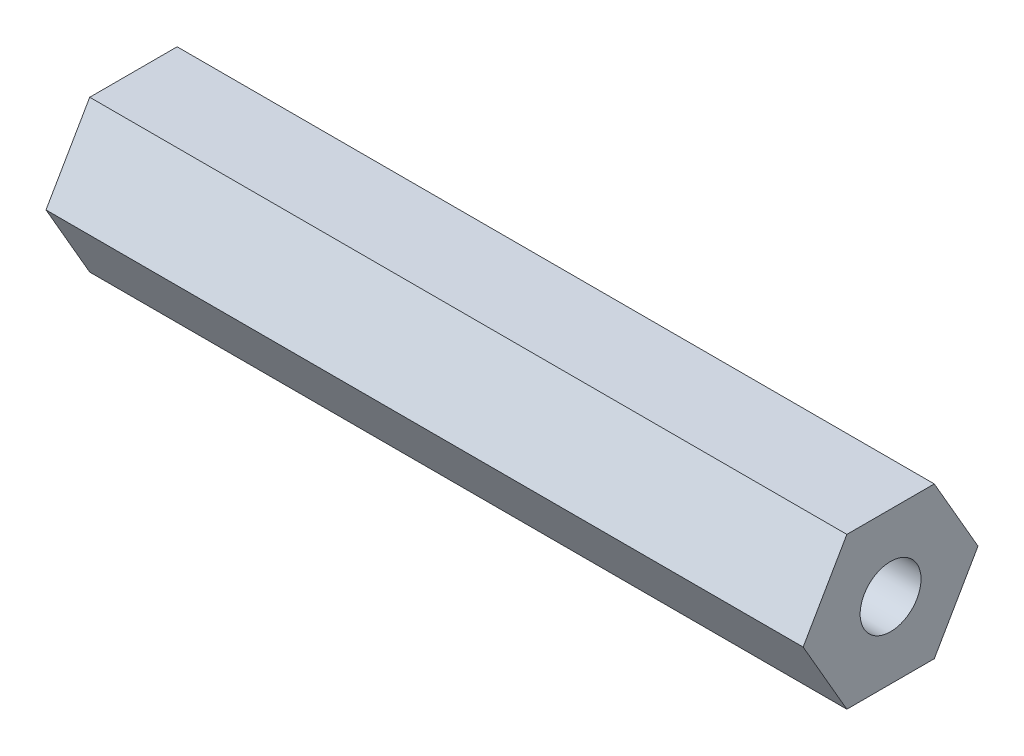
SolidWorks part; units mm, degrees
material "Plain Carbon Steel"
ref_plane "Front Plane" through (0, 0, 0) normal (0, 0, 1) x (1, 0, 0)
ref_plane "Top Plane" through (0, 0, 0) normal (0, 1, 0) x (1, 0, 0)
ref_plane "Right Plane" through (0, 0, 0) normal (1, 0, 0) x (0, 0, -1)
sketch "Sketch1" plane through (0, 0, 0) normal (1, 0, 0) x (0, 0, -1)
  line L1 (7.3323, 0) -> (3.6662, 6.35)
  line L2 (3.6662, 6.35) -> (-3.6662, 6.35)
  line L3 (-3.6662, 6.35) -> (-7.3323, 0)
  line L4 (-7.3323, 0) -> (-3.6662, -6.35)
  line L5 (-3.6662, -6.35) -> (3.6662, -6.35)
  line L6 (3.6662, -6.35) -> (7.3323, 0)
  circle A0 centre (0, 0) radius 6.35 construction
  dimension "D1" = 12.7
extrude "Boss-Extrude1" add sketch "Sketch1" along normal blind 63.5
hole_wizard "1/4-20 Tapped Hole1" positions "Sketch3" profile "Sketch4" tap size "1/4-20" standard "ANSI Inch"
sketch "Sketch3" plane through (63.5, 0, 0) normal (1, 0, 0) x (0, 0, -1)
  point P0 (0, 0)
cosmetic thread "Hole Thread1" parameters "D1"=12.7, "D2"=6.35
sketch "Sketch4" plane through (63.5, 0, 0) normal (0, 1, 0) x (0, 0, -1)
  line L0 (0, 0) -> (0, 18.0438)
  line L1 (0, 18.0438) -> (2.5527, 16.51)
  line L2 (2.5527, 16.51) -> (2.5527, 0)
  line L5 (2.5527, 0) -> (0, 0)
  line L10 (0, 18.0438) -> (-2.5527, 16.51) construction
  line L11 (0, -6.35) -> (0, 107.95) construction
  dimension "Tap Drill Dia." = 5.1054
  dimension "Tap Drill Depth" = 16.51
  dimension "Drill Angle" = 118
hole_wizard "1/4-20 Tapped Hole2" positions "Sketch5" profile "Sketch6" tap size "1/4-20" standard "ANSI Inch"
sketch "Sketch5" plane through (0, 0, 0) normal (-1, 0, 0) x (0, 0, 1)
  point P0 (0, 0)
sketch "Sketch6" plane through (0, 0, 0) normal (0, 1, 0) x (0, 0, 1)
  line L0 (0, 0) -> (0, 18.0438)
  line L1 (0, 18.0438) -> (2.5527, 16.51)
  line L2 (2.5527, 16.51) -> (2.5527, 0)
  line L5 (2.5527, 0) -> (0, 0)
  line L10 (0, 18.0438) -> (-2.5527, 16.51) construction
  line L11 (0, -6.35) -> (0, 107.95) construction
  dimension "Tap Drill Dia." = 5.1054
  dimension "Tap Drill Depth" = 16.51
  dimension "Drill Angle" = 118
cosmetic thread "Hole Thread2" parameters "D1"=12.7, "D2"=6.35
